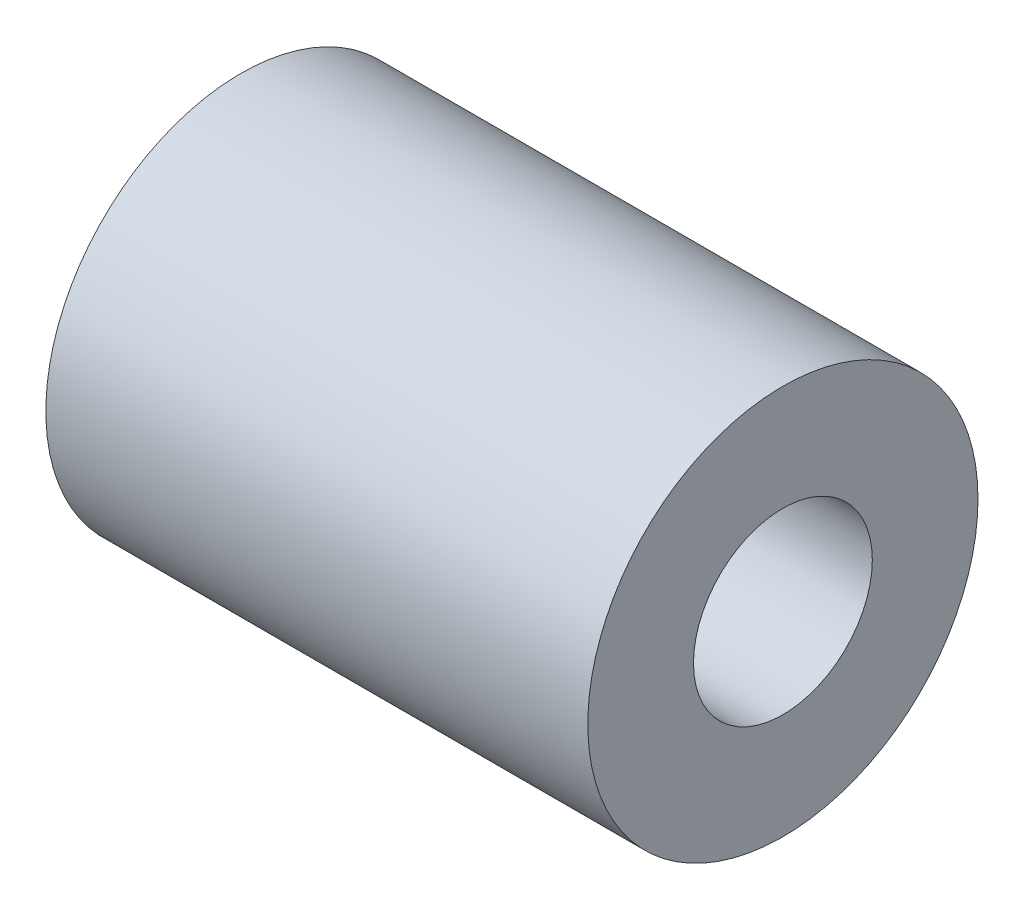
SolidWorks part; units mm, degrees
material "ABS"
ref_plane "前视基准面" through (0, 0, 0) normal (0, 0, 1) x (1, 0, 0)
ref_plane "上视基准面" through (0, 0, 0) normal (0, 1, 0) x (1, 0, 0)
ref_plane "右视基准面" through (0, 0, 0) normal (1, 0, 0) x (0, 0, -1)
other "Configuration Table"
sketch "草图1" plane through (0, 0, 0) normal (1, 0, 0) x (0, 0, -1)
  circle A0 centre (0, 0) radius 1.65
  circle A1 centre (0, 0) radius 3.6
  dimension "D1" = 3.3
  dimension "D2" = 7.2
extrude "凸台-拉伸1" add sketch "草图1" along normal blind 10
